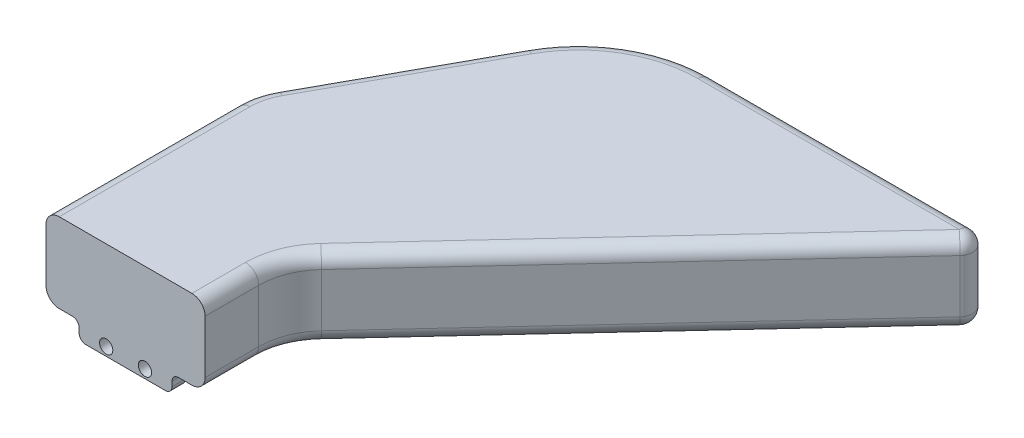
SolidWorks part; units mm, degrees
ref_plane "Front Plane" through (0, 0, 0) normal (0, 0, 1) x (1, 0, 0)
ref_plane "Top Plane" through (0, 0, 0) normal (0, 1, 0) x (1, 0, 0)
ref_plane "Right Plane" through (0, 0, 0) normal (1, 0, 0) x (0, 0, -1)
sketch "Sketch1" plane through (0, 0, 0) normal (0, 1, 0) x (1, 0, 0)
  line L0 (-30.6143, 0) -> (0, 0) construction
  line L1 (0, 0) -> (0, 18.9605) construction
  line L2 (-11.3817, 10.7916) -> (-4.7124, 22.9251)
  line L3 (0, 0) -> (30.6143, 0) construction
  line L4 (4.051, 28.1082) -> (23.7653, 28.1082)
  line L5 (24.4987, 26.4284) -> (1.3331, 1.4381)
  line L7 (-12, 8.3832) -> (-12, -6)
  line L8 (-12, -6) -> (0, -6)
  line L9 (0, -6) -> (0, -1.961)
  arc A0 (4.051, 28.1082) -> (-4.7124, 22.9251) centre (4.051, 18.1082) ccw
  arc A1 (24.4987, 26.4284) -> (23.7653, 28.1082) centre (23.7653, 27.1082) ccw
  arc A2 (1.3331, 1.4381) -> (0, -1.961) centre (5, -1.961) ccw
  arc A3 (-12, 8.3832) -> (-11.3817, 10.7916) centre (-7, 8.3832) cw
  dimension "D1" = 6
  dimension "D3" = 10
  dimension "D4" = 1
  dimension "D5" = 5
  dimension "D6" = 5
  dimension "D2" = 12
extrude "Boss-Extrude1" add sketch "Sketch1" along normal blind 6
fillet "Fillet1" radius 1 9 edges at (0, 6, 3.9805) (0.3452, 6, 0.1354) (12.9159, 6, -13.9333) (24.6818, 6, -27.5083) (13.9082, 6, -28.1082) (-1.0397, 6, -26.7154) (-8.0471, 6, -16.8584) (-11.843, 6, -9.6265) (-12, 6, -1.1916)
fillet "Fillet2" radius 1 9 edges at (-11.843, 0, -9.6265) (-8.0471, 0, -16.8584) (-1.0397, 0, -26.7154) (13.9082, 0, -28.1082) (24.6818, 0, -27.5083) (12.9159, 0, -13.9333) (0.3452, 0, 0.1354) (-12, 0, -1.1916) (0, 0, 3.9805)
ref_plane "Plane1" through (0, 0, 0) normal (0, 0, 1) x (1, 0, 0)
sketch "Sketch3" plane through (0, 0, 6) normal (0, 0, 1) x (1, 0, 0)
  line L0 (-6, 6) -> (-6, 10.8641) construction
  line L1 (-11, 6) -> (-1, 6) construction
  line L2 (-9.5, 6) -> (-9.5, 7.35)
  line L3 (-9.5, 7.35) -> (-2.5, 7.35)
  line L4 (-2.5, 6) -> (-2.5, 7.35)
  line L5 (-9.5, 6) -> (-2.5, 6)
  line L6 (-12, 3) -> (0, 3) construction
  line L7 (-12, 5) -> (-12, 1) construction
  line L8 (0, 5) -> (0, 1) construction
  line L9 (-9.5, 0) -> (-2.5, 0)
  line L10 (-2.5, 0) -> (-2.5, -1.35)
  line L11 (-9.5, -1.35) -> (-2.5, -1.35)
  line L12 (-9.5, 0) -> (-9.5, -1.35)
  line L13 (-6, -1.35) -> (-6, 3) construction
  circle A0 centre (-4.6307, -0.7001) radius 0.5
  circle A1 centre (-7.3693, -0.7001) radius 0.5
  point P9 (-6, 7.35)
  point P19 (-6, -1.35)
  dimension "D3" = 1
  dimension "D1" = 1.35
  dimension "D2" = 7
  dimension "D4" = 0.7001
extrude "Boss-Extrude3" add sketch "Sketch3" against normal blind 1 contours L12 L11 L10 L9
fillet "Fillet5" radius 0.5 4 edges at (-9.5, -1.35, 5.5) (-9.5, 0, 5.5) (-2.5, -1.35, 5.5) (-2.5, 0, 5.5)
sketch "Sketch6" plane through (0, 0, 6) normal (0, 0, 1) x (1, 0, 0)
  line L0 (-6, -1.35) -> (-6, 0.3243) construction
  line L1 (-9, -1.35) -> (-3, -1.35) construction
  line L2 (-2, 0) -> (-10, 0)
  circle A0 centre (-4.5381, -0.7) radius 0.5
  circle A1 centre (-7.4619, -0.7) radius 0.5
  dimension "D1" = 1
  dimension "D2" = 0.7
extrude "Cut-Extrude2" cut sketch "Sketch6" against normal blind 1 contours A1 | A0
